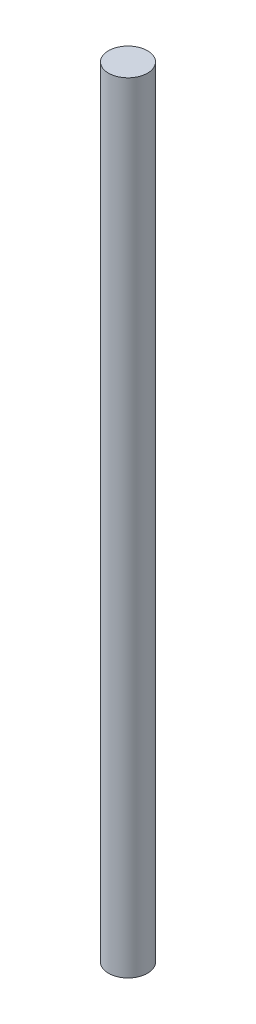
SolidWorks part; units mm, degrees
ref_plane "Alzado" through (0, 0, 0) normal (0, 0, 1) x (1, 0, 0)
ref_plane "Planta" through (0, 0, 0) normal (0, 1, 0) x (1, 0, 0)
ref_plane "Vista lateral" through (0, 0, 0) normal (1, 0, 0) x (0, 0, -1)
sketch "Croquis1" plane through (0, 0, 0) normal (0, 1, 0) x (1, 0, 0)
  circle A0 centre (0, 0) radius 2.5
  dimension "D1" = 5
extrude "Saliente-Extruir1" add sketch "Croquis1" along normal blind 100
